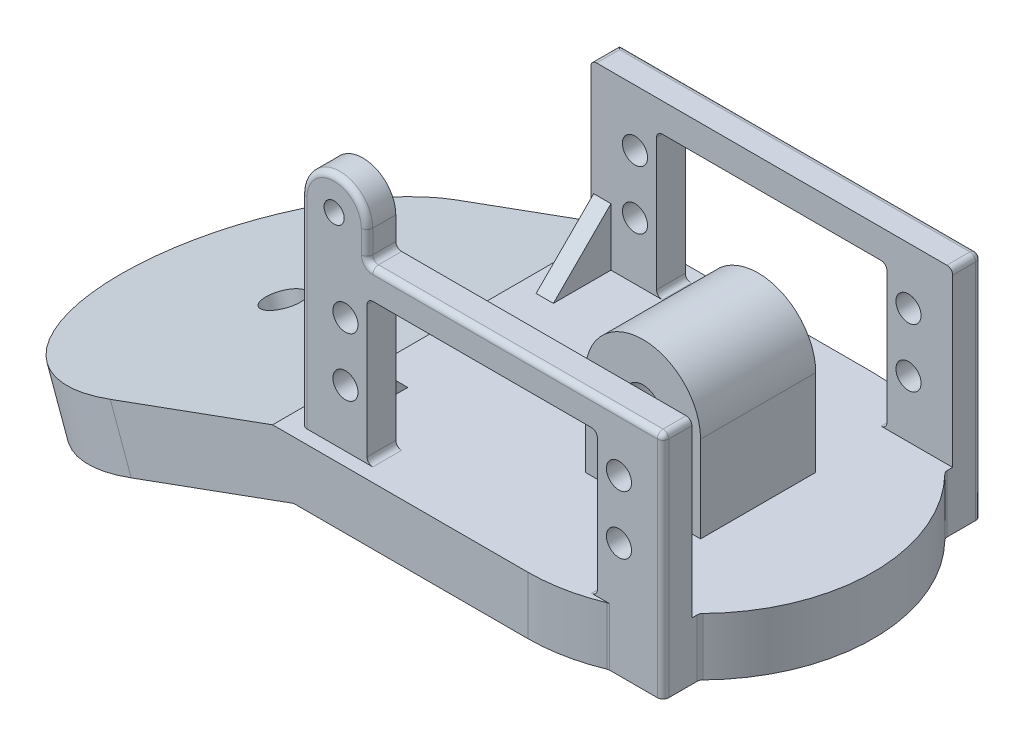
SolidWorks part; units mm, degrees
ref_plane "Plan de face" through (0, 0, 0) normal (0, 0, 1) x (1, 0, 0)
ref_plane "Plan de dessus" through (0, 0, 0) normal (0, 1, 0) x (1, 0, 0)
ref_plane "Plan de droite" through (0, 0, 0) normal (1, 0, 0) x (0, 0, -1)
sketch "Esquisse5" plane through (0, 0, 0) normal (0, 1, 0) x (1, 0, 0)
  line L0 (42.5, 0) -> (-42.5, 0) construction
  line L1 (42.5, -30) -> (-42.5, -30)
  line L2 (42.5, 30) -> (-42.5, 30)
  arc A0 (42.5, -30) -> (42.5, 30) centre (42.5, 0) ccw
  arc A1 (-42.5, 30) -> (-42.5, -30) centre (-42.5, 0) ccw
  point P2 (0, 0)
  dimension "D2" = 30
  dimension "D1" = 85
extrude "Boss.-Extru.3" add sketch "Esquisse5" along normal mid plane 10
sketch "Esquisse36" plane through (0, 0, 0) normal (0, 0, 1) x (1, 0, 0)
  line L0 (0, 0) -> (9.0993, -25)
  line L1 (9.0993, -25) -> (-112.5, -25)
  line L2 (-112.5, -25) -> (-112.5, 35)
  line L3 (-112.5, 35) -> (-12.739, 35)
  line L4 (-12.739, 35) -> (0, 0)
  line L5 (42.5, -5) -> (-42.5, -5) construction
  line L6 (42.5, 5) -> (-42.5, 5) construction
  line L7 (-42.5, 5) -> (-42.5, -5) construction
  dimension "D1" = 180
  dimension "D2" = 20
  dimension "D3" = 70
  dimension "D4" = 30
  dimension "D5" = 70
sketch "Esquisse7" plane through (0, 0, 0) normal (0, 0, 1) x (1, 0, 0)
  line L0 (42.5, 5) -> (32.5, 5)
  line L1 (-42.5, 5) -> (42.5, 5) construction
  line L2 (32.5, 5) -> (32.5, 20)
  line L3 (32.5, 20) -> (52.5, 20)
  line L4 (52.5, 20) -> (52.5, 5)
  line L5 (72.5, 5) -> (42.5, 5) construction
  line L6 (52.5, 5) -> (42.5, 5)
  arc A0 (32.5, 20) -> (52.5, 20) centre (42.5, 20) cw
  circle A1 centre (42.5, 20) radius 3.175
  dimension "D1" = 10
  dimension "D3" = 6.35
  dimension "D2" = 15
extrude "Boss.-Extru.5" add sketch "Esquisse7" along normal mid plane 20 contours A1 L3 A0 | A1 L3 L2 L0 L6 L4
sketch "Esquisse10" plane through (0, -5, 0) normal (0, -1, 0) x (1, 0, 0)
  point P0 (42.5, 0)
ref_plane "Plan1" through (0, 0, 22.64) normal (0, 0, 1) x (1, 0, 0)
sketch "Esquisse13" plane through (0, 0, 22.64) normal (0, 0, 1) x (1, 0, 0)
  line L0 (-42.5, 5) -> (42.5, 5) construction
  line L1 (5.8, 5) -> (58.63, 5)
  line L2 (5.8, 5) -> (5.8, 29.91) construction
  line L3 (5.8, 29.91) -> (58.63, 29.91) construction
  line L4 (58.63, 5) -> (58.63, 29.91) construction
  line L5 (5.8, 5) -> (0.8, 5)
  line L6 (0.8, 5) -> (0.8, 34.91)
  line L7 (0.8, 34.91) -> (63.63, 34.91)
  line L8 (63.63, 34.91) -> (63.63, 5)
  line L9 (63.63, 5) -> (58.63, 5)
  line L10 (63.63, 5) -> (58.63, 5)
  line L11 (0.8, 5) -> (5.8, 5)
  line L12 (12.215, 5) -> (12.215, 29.91)
  line L13 (12.215, 29.91) -> (52.215, 29.91)
  line L14 (52.215, 29.91) -> (52.215, 5)
  line L15 (52.215, 5) -> (12.215, 5)
  circle A0 centre (42.5, 20) radius 3.175 construction
  circle A2 centre (55.97, 25.08) radius 2.18
  circle A3 centre (55.97, 14.92) radius 2.18
  circle A4 centre (8.47, 25.08) radius 2.18
  circle A5 centre (8.47, 14.92) radius 2.18
  point P6 (58.63, 17.455)
  point P24 (32.215, 29.91)
  point P26 (32.215, 34.91)
  dimension "D4" = 5
  dimension "D7" = 4.36
  dimension "D8" = 47.5
  dimension "D12" = 10.16
  dimension "D1" = 52.83
  dimension "D2" = 16.13
  dimension "D3" = 24.91
  dimension "D5" = 4.83
  dimension "D6" = 2.67
  dimension "D9" = 47.5
  dimension "D10" = 0
  dimension "D11" = 0
  dimension "D13" = 0
  dimension "D14" = 5
  dimension "D15" = 5
  dimension "D16" = 40
  dimension "D17" = 0
  dimension "D18" = 0
extrude "Boss.-Extru.8" add sketch "Esquisse13" along normal blind 5 contours L13 L14 L1 L9 L8 L7 L6 L5 L12 A5 A4 A3 A2
ref_plane "Plan12" through (2.8, 0, 0) normal (-1, 0, 0) x (0, 0, 1)
mirror "Symétrie2" about plane through (0, 0, 0) normal (0, 0, 1) of "Boss.-Extru.8"
sketch "Esquisse14" plane through (0, 0, 0) normal (0, 0, 1) x (1, 0, 0)
  point P0 (42.5, 20)
sketch "Esquisse33" plane through (0, 5, 0) normal (0, -1, 0) x (1, 0, 0)
  line L0 (54.1632, -27.64) -> (63.63, -27.64) construction
  line L1 (63.63, 27.64) -> (54.1632, 27.64)
  line L2 (63.63, 27.64) -> (63.63, -27.64)
  line L3 (63.63, -27.64) -> (54.1632, -27.64)
  line L4 (54.1632, 27.64) -> (54.1632, -27.64)
  dimension "D1" = 0
  dimension "D2" = 0
extrude "Boss.-Extru.10" add sketch "Esquisse33" along normal up to surface (10 mm away) up to face at (0, -5, 0)
sketch "Esquisse34" plane through (0, 0, 0) normal (0, 1, 0) x (1, 0, 0)
  line L0 (0, 0) -> (0, 29.4868) construction
extrude "Enlèv. mat.-Extru.6" cut sketch "Esquisse36" against normal mid plane 130
ref_plane "Plan11" through (0, 0, 0) normal (-0.342, 0.9397, 0) x (0, 0, -1)
sketch "Esquisse35" plane through (0, 0, 0) normal (-0.342, 0.9397, 0) x (0, 0, -1)
  circle A0 centre (0, 30) radius 30
  dimension "D1" = 60
  dimension "D2" = 0
extrude "Boss.-Extru.11" add sketch "Esquisse35" along normal mid plane 10.64
sketch "Esquisse37" plane through (0, 0, 0) normal (0, 0, 1) x (1, 0, 0)
sketch "Esquisse38" plane through (-1.8195, 4.9992, 0) normal (-0.342, 0.9397, 0) x (0.9397, 0.342, 0)
  point P1 (-30, 0)
sketch "Esquisse39" plane through (1.8195, -4.9992, 0) normal (0.342, -0.9397, 0) x (0.9397, 0.342, 0)
  point P0 (-30, 0)
sketch "Esquisse40" plane through (0, 0, 0) normal (0, 0, 1) x (1, 0, 0)
  line L0 (-26.3712, -15.2598) -> (-30.0103, -5.2614)
  line L1 (-26.3712, -15.2598) -> (1.8195, -4.9992)
  line L2 (-30.0103, -5.2614) -> (-1.8195, 4.9992)
  line L3 (1.8195, -4.9992) -> (-1.8195, 4.9992)
  dimension "D1" = 0
extrude "Boss.-Extru.12" add sketch "Esquisse40" along normal mid plane 60
sketch "Esquisse41" plane through (-1.8195, 4.9992, 0) normal (-0.342, 0.9397, 0) x (0.9397, 0.342, 0)
  circle A0 centre (-30, 0) radius 3.175
  dimension "D1" = 6.35
extrude "Enlèv. mat.-Extru.7" cut sketch "Esquisse41" against normal blind 60
sketch "Esquisse42" plane through (0, 0, 27.64) normal (0, 0, 1) x (1, 0, 0)
  line L0 (0.8, 34.91) -> (0.8, 39.91)
  line L1 (0.8, 39.91) -> (12.215, 39.91)
  line L2 (12.215, 39.91) -> (12.215, 34.91)
  line L3 (0.8, 34.91) -> (63.63, 34.91) construction
  line L4 (12.215, 34.91) -> (0.8, 34.91)
  line L5 (12.215, 5) -> (12.215, 29.91) construction
  arc A0 (0.8, 39.91) -> (12.215, 39.91) centre (6.5075, 39.91) cw
  circle A1 centre (6.5075, 39.91) radius 1.75
  line M15 (63.63, 34.91) -> (0.8, 34.91)
  dimension "D3" = 3.5
  dimension "D1" = 5
  dimension "D2" = 0
extrude "Boss.-Extru.13" add sketch "Esquisse42" against normal up to surface (5 mm away) contours A1 L1 A0 | A1 L1 L0 L2 M15
sketch "Esquisse45" plane through (2.8, 0, 0) normal (-1, 0, 0) x (0, 0, 1)
  line L0 (22.64, 14.9996) -> (12.64, 4.9996)
  line L1 (22.64, 5) -> (22.64, 39.91) construction
  line L2 (30, 4.9996) -> (-30, 4.9996) construction
  dimension "D1" = 10
  dimension "D2" = 10
rib "Nervure4" sketch "Esquisse45" sketch "Esquisse45" thickness 3 extrusion direction parallel to sketch draft on no parameters "D1"=3
fillet "Congé1" radius 1 6 edges at (54.1632, 0, 27.64) (63.63, 14.955, 27.64) (63.63, 0, 21.2961) (54.1632, 0, -27.64) (63.63, 0, -21.2961) (63.63, 14.955, -27.64)
mirror "Symétrie3" about plane through (0, 0, 0) normal (0, 0, 1) of "Nervure4"
fillet "Congé2" radius 1 18 edges at (63.63, 34.91, 24.64) (63.3371, 34.91, 27.3471) (63.63, 34.91, -24.64) (63.3371, 34.91, -27.3471) (52.215, 5, 25.14) (12.215, 5, -25.14) (12.215, 29.91, 25.14) (52.215, 29.91, 25.14) (0.8, 22.455, 27.64) (12.215, 5, 25.14) (52.215, 29.91, -25.14) (12.215, 29.91, -25.14) (0.8, 34.91, -25.14) (52.215, 5, -25.14) (31.715, 34.91, -27.64) (37.4225, 34.91, 27.64) (6.5075, 45.6175, 27.64) (12.215, 34.91, 25.14)
